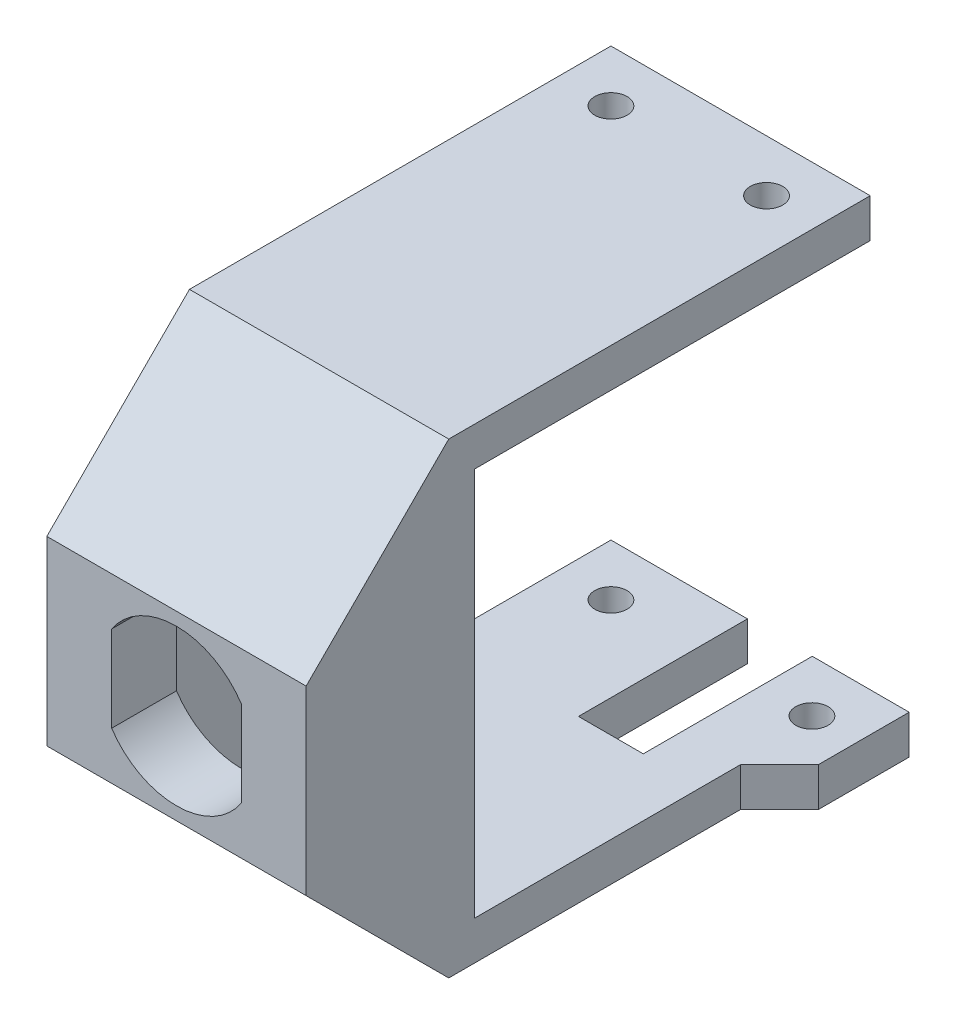
SolidWorks part; units mm, degrees
ref_plane "前视基准面" through (0, 0, 0) normal (0, 0, 1) x (1, 0, 0)
ref_plane "上视基准面" through (0, 0, 0) normal (0, 1, 0) x (1, 0, 0)
ref_plane "右视基准面" through (0, 0, 0) normal (1, 0, 0) x (0, 0, -1)
other "Configuration Table"
ref_plane "基准面1" through (0, 0, 45) normal (0, 0, 1) x (1, 0, 0)
sketch "草图2" plane through (0, 0, 38.51) normal (0, 0, 1) x (1, 0, 0)
  line L0 (81.9336, 6) -> (118.8757, 6) construction
  line L1 (89.3, 15) -> (109.3, 15)
  line L2 (104.3, -3.3166) -> (104.3, 3.3166)
  line L3 (94.3, 3.3166) -> (94.3, -3.3166)
  line L4 (104.3, -3.3166) -> (104.3, 3.3166)
  line L5 (94.3, 3.3166) -> (94.3, -3.3166)
  line L6 (89.3, 15) -> (89.3, -15)
  line L7 (89.3, -15) -> (109.3, -15)
  line L8 (109.3, 15) -> (109.3, -15)
  line L9 (89.3, 15) -> (109.3, -15) construction
  line L10 (89.3, -15) -> (109.3, 15) construction
  line L11 (79.3, 15) -> (107.3, 15) construction
  arc A2 (94.3, -3.3166) -> (104.3, -3.3166) centre (99.3, 0) ccw
  arc A3 (104.3, 3.3166) -> (94.3, 3.3166) centre (99.3, 0) ccw
  arc A4 (94.3, -3.3166) -> (104.3, -3.3166) centre (99.3, 0) ccw
  arc A5 (104.3, 3.3166) -> (94.3, 3.3166) centre (99.3, 0) ccw
  dimension "D2" = 5
  dimension "D1" = 0
extrude "凸台-拉伸1" add sketch "草图2" along normal blind 5
sketch "草图5" plane through (0, 0, 43.51) normal (0, 0, 1) x (1, 0, 0)
  line L1 (89.3, -15) -> (109.3, -15)
  line L2 (89.3, -15) -> (89.3, -18)
  line L3 (89.3, -18) -> (109.3, -18)
  line L4 (109.3, -15) -> (109.3, -18)
  line L5 (109.3, -15) -> (109.3, 15) construction
  line L6 (89.3, 15) -> (109.3, 15)
  line L7 (89.3, 15) -> (89.3, 18)
  line L8 (89.3, 18) -> (109.3, 18)
  line L9 (109.3, 15) -> (109.3, 18)
  line L10 (109.3, 15) -> (89.3, 15) construction
  line M2 (109.3, 15) -> (89.3, 15)
  line M4 (89.3, -15) -> (109.3, -15)
  dimension "D1" = 3
  dimension "D2" = 3
extrude "凸台-拉伸3" add sketch "草图5" against normal up to surface (43.51 mm away) contours L9 L8 L7 M2 | L4 L2 L3 M4 up to plane "前视基准面"
sketch "草图6" plane through (0, -18, 0) normal (0, -1, 0) x (1, 0, 0)
  line L0 (109.3, 0) -> (89.3, 0) construction
  line L1 (99.8297, 1.0966) -> (104.8297, 1.0966)
  line L2 (99.8297, 1.0966) -> (99.8297, 0)
  line L3 (99.8297, 0) -> (104.8297, 0)
  line L4 (104.8297, 1.0966) -> (104.8297, 9.6924)
  line L5 (104.8297, 9.6924) -> (99.8297, 9.6924)
  line L6 (99.8297, 9.6924) -> (99.8297, 1.0966)
  line L7 (99.8297, 1.0966) -> (104.8297, 1.0966)
  line L8 (104.8297, 1.0966) -> (104.8297, 9.6924)
  line L10 (99.8297, 9.6924) -> (99.8297, 1.0966)
  line L11 (99.8297, 1.0966) -> (104.8297, 1.0966)
  line L12 (104.8297, 9.5819) -> (104.8297, 14.535)
  line L13 (99.8297, 9.5819) -> (104.8297, 9.5819)
  line L14 (99.8297, 14.535) -> (99.8297, 9.5819)
  line L15 (104.8297, 14.535) -> (99.8297, 14.535)
  line L16 (104.8297, 9.5819) -> (104.8297, 14.535)
  line L18 (99.8297, 14.535) -> (99.8297, 9.5819)
  line L19 (104.8297, 14.535) -> (99.8297, 14.535)
  line L20 (104.8297, 1.0966) -> (104.8297, 0)
  line L21 (99.8297, 13.035) -> (104.8297, 13.035)
  line M5 (89.3, 0) -> (109.3, 0)
  dimension "D3" = 1.5
  dimension "D1" = 0
  dimension "D2" = 0
extrude "切除-拉伸2" cut sketch "草图6" against normal up to next contours L21 L18 L10 L1 L8 L16 | L20 L1 L2 M5
sketch "草图7" plane through (0, -18, 0) normal (0, -1, 0) x (1, 0, 0)
  line L0 (109.3, 10) -> (112.3027, 6.9973)
  line L1 (109.3, 0) -> (109.3, 43.51) construction
  line L2 (112.3027, 6.9973) -> (112.3027, 0)
  line L3 (112.3027, 0) -> (109.3, 0)
  line L4 (109.3, 10) -> (109.3, 0)
  dimension "D1" = 3.0027
  dimension "D2" = 45
  dimension "D3" = 10
extrude "凸台-拉伸4" add sketch "草图7" against normal up to surface (3 mm away)
sketch "草图8" plane through (0, -18, 0) normal (0, -1, 0) x (1, 0, 0)
  line L1 (99.8297, 0) -> (89.3, 0) construction
  line L2 (89.3, 0) -> (89.3, 43.51) construction
  line L3 (112.3027, 0) -> (104.8297, 0) construction
  line L4 (112.3027, 0) -> (112.3027, 6.9973) construction
  circle A0 centre (93.3, 4) radius 1.25
  circle A1 centre (108.8027, 4) radius 1.25
  dimension "D1" = 2.5
  dimension "D5" = 3.5
  dimension "D6" = 2.5
  dimension "D2" = 4
  dimension "D3" = 4
  dimension "D4" = 4
extrude "切除-拉伸3" cut sketch "草图8" against normal up to next
sketch "草图9" plane through (0, 18, 0) normal (0, 1, 0) x (1, 0, 0)
  line L0 (109.3, 0) -> (109.3, -43.51) construction
  line L1 (109.3, 0) -> (89.3, 0) construction
  line L2 (89.3, 0) -> (89.3, -43.51) construction
  circle A0 centre (105.3, -4) radius 1.25
  circle A1 centre (93.3, -4) radius 1.25
  dimension "D1" = 2.5
  dimension "D2" = 2.5
  dimension "D3" = 4
  dimension "D4" = 4
  dimension "D5" = 4
extrude "切除-拉伸4" cut sketch "草图9" against normal up to next
chamfer "倒角2" distance 8 2 edges at (99.3, -15, 38.51) (99.3, 15, 38.51)
chamfer "倒角3" distance 11 2 edges at (99.3, 18, 43.51) (99.3, -18, 43.51)
ref_plane "基准面2" through (99.3, 0, 0) normal (1, 0, 0) x (0, 0, -1)
sketch "草图14" plane through (89.3, 0, 0) normal (-1, 0, 0) x (0, 0, 1)
  line L0 (38.51, -7) -> (30.51, -15) construction
  line L1 (38.51, 7) -> (38.51, -7) construction
  line L2 (30.51, 15) -> (38.51, 7) construction
  line L3 (38.51, -7) -> (30.51, -15)
  line L4 (38.51, 7) -> (38.51, -7)
  line L5 (30.51, 15) -> (38.51, 7)
  line L6 (30.51, 15) -> (30.51, -15)
extrude "凸台-拉伸6" add sketch "草图14" against normal blind 3
mirror "镜向1" about plane through (99.3, 0, 0) normal (1, 0, 0) of "凸台-拉伸6"
